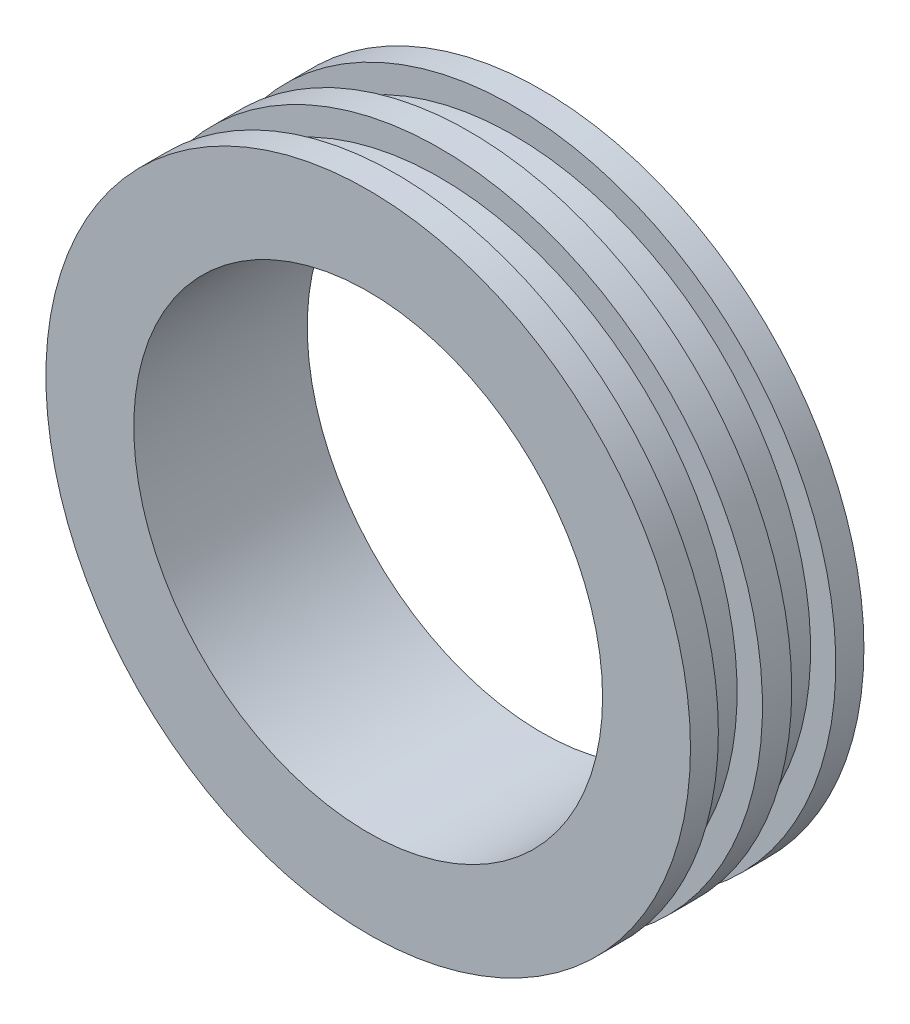
SolidWorks part; units mm, degrees
ref_plane "Front Plane" through (0, 0, 0) normal (0, 0, 1) x (1, 0, 0)
ref_plane "Top Plane" through (0, 0, 0) normal (0, 1, 0) x (1, 0, 0)
ref_plane "Right Plane" through (0, 0, 0) normal (1, 0, 0) x (0, 0, -1)
sketch "Sketch4" plane through (0, 0, 0) normal (0, 1, 0) x (1, 0, 0)
  line L0 (0, 0) -> (0, -25.4) construction
sketch "Sketch1" plane through (0, 0, 0) normal (0, 0, 1) x (1, 0, 0)
  circle A0 centre (0, 0) radius 34.925
  circle A1 centre (0, 0) radius 25.4
extrude "Boss-Extrude1" add sketch "Sketch1" along normal blind 18.796
sketch "groove" plane through (0, 0, 0) normal (1, 0, 0) x (0, 0, -1)
  line L0 (-15.7734, 34.9876) -> (-15.7734, 32.1936)
  line L1 (-15.7734, 32.1936) -> (-11.0109, 32.1936)
  line L2 (-11.0109, 32.1936) -> (-10.9982, 34.9876)
  line L3 (-10.9982, 34.9876) -> (-7.8232, 34.9876)
  line L4 (-7.8232, 34.9876) -> (-7.8232, 32.1936)
  line L5 (-7.8232, 32.1936) -> (-3.048, 32.1936)
  line L6 (-3.048, 32.1936) -> (-3.048, 34.9876)
  line L7 (-15.7734, 38.1258) -> (-3.048, 38.1258)
  line L8 (-3.048, 38.1258) -> (-3.048, 34.9876)
  line L9 (0, 34.9876) -> (-25.3296, 34.9876) construction
  line L10 (0, -34.925) -> (0, 34.925) construction
  line L13 (-15.7734, 38.1258) -> (-15.7734, 34.9876)
  dimension "D1" = 2.794
  dimension "D2" = 3.048
  dimension "D4" = 4.7752
  dimension "D5" = 4.7752
  dimension "D6" = 3.175
ref_plane "Plane1" through (0, 0, 11.0109) normal (0, 0, 1) x (1, 0, 0)
sketch "groove path" plane through (0, 0, 11.0109) normal (0, 0, 1) x (1, 0, 0)
  circle A0 centre (0, 0) radius 34.925 construction
  circle A1 centre (0, 0) radius 34.925
sweep "Cut-Sweep1" cut profiles "groove" path "groove path"
